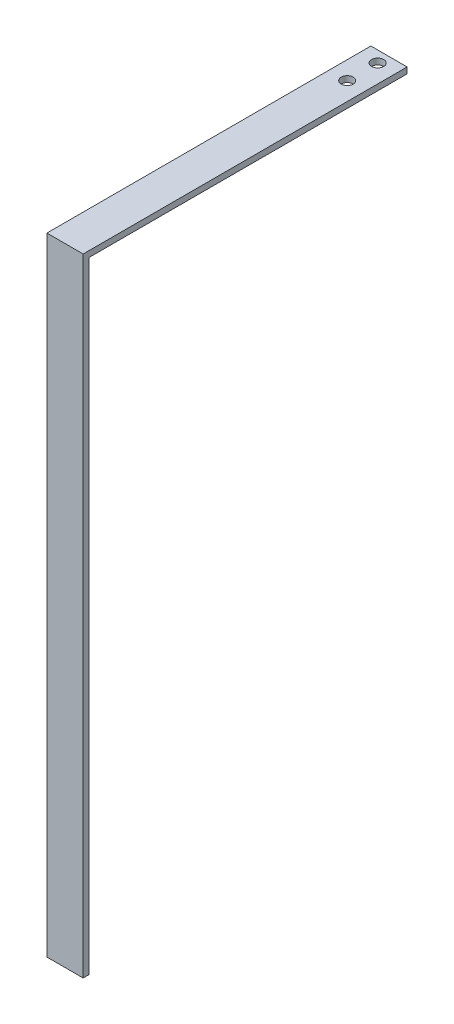
SolidWorks part; units mm, degrees
ref_plane "Alzado" through (0, 0, 0) normal (0, 0, 1) x (1, 0, 0)
ref_plane "Planta" through (0, 0, 0) normal (0, 1, 0) x (1, 0, 0)
ref_plane "Vista lateral" through (0, 0, 0) normal (1, 0, 0) x (0, 0, -1)
sketch "Croquis1" plane through (0, 0, 0) normal (0, 0, 1) x (1, 0, 0)
  line L1 (-19.05, 3.155) -> (19.05, 3.155)
  line L2 (-19.05, 3.155) -> (-19.05, -3.155)
  line L3 (-19.05, -3.155) -> (19.05, -3.155)
  line L4 (19.05, 3.155) -> (19.05, -3.155)
  line L5 (-19.05, 3.155) -> (19.05, -3.155) construction
  line L6 (-19.05, -3.155) -> (19.05, 3.155) construction
  point P0 (0, 0)
  dimension "D1" = 38.1
  dimension "D2" = 6.31
extrude "Saliente-Extruir1" add sketch "Croquis1" along normal blind 340.39
sketch "Croquis3" plane through (0, -3.155, 0) normal (0, -1, 0) x (1, 0, 0)
  line L1 (19.05, 334.08) -> (-19.05, 334.08)
  line L2 (19.05, 334.08) -> (19.05, 340.39)
  line L3 (19.05, 340.39) -> (-19.05, 340.39)
  line L4 (-19.05, 334.08) -> (-19.05, 340.39)
  line L5 (19.05, 334.08) -> (-19.05, 340.39) construction
  line L6 (19.05, 340.39) -> (-19.05, 334.08) construction
  point P0 (0, 337.235)
  dimension "D1" = 6.31
extrude "Saliente-Extruir2" add sketch "Croquis3" along normal blind 652.48
sketch "Croquis4" plane through (0, 0, 340.39) normal (0, 0, 1) x (1, 0, 0)
  line L0 (-19.05, -655.635) -> (19.05, -655.635)
  line L1 (19.05, -655.635) -> (19.05, -661.945)
  line L2 (19.05, -661.945) -> (-19.05, -661.945)
  line L3 (-19.05, -661.945) -> (-19.05, -655.635)
  dimension "D1" = 6.31
sketch "Croquis5" plane through (0, 3.155, 0) normal (0, 1, 0) x (1, 0, 0)
  circle A0 centre (0, -43.8922) radius 6.35
  circle A1 centre (0, -11.8922) radius 6.35
extrude "Cortar-Extruir1" cut sketch "Croquis5" against normal blind 6.31
